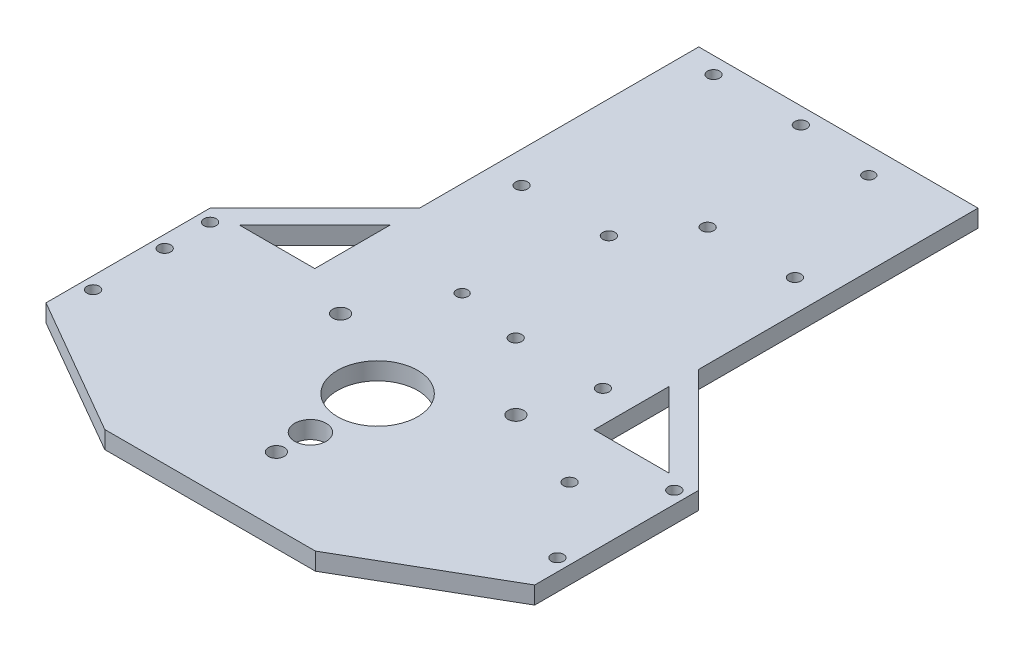
SolidWorks part; units mm, degrees
ref_plane "前视基准面" through (0, 0, 0) normal (0, 0, 1) x (1, 0, 0)
ref_plane "上视基准面" through (0, 0, 0) normal (0, 1, 0) x (1, 0, 0)
ref_plane "右视基准面" through (0, 0, 0) normal (1, 0, 0) x (0, 0, -1)
sketch "草图1" plane through (0, 0, 0) normal (0, 1, 0) x (1, 0, 0)
  line L1 (-40, 90) -> (40, 90)
  line L2 (-40, 90) -> (-40, -90)
  line L3 (-40, -90) -> (40, -90)
  line L4 (40, 90) -> (40, -90)
  line L5 (-40, 90) -> (40, -90) construction
  line L6 (-40, -90) -> (40, 90) construction
  point P0 (0, 0)
  dimension "D1" = 80
  dimension "D2" = 180
extrude "凸台-拉伸1" add sketch "草图1" along normal blind 5
sketch "草图2" plane through (0, 5, 0) normal (0, 1, 0) x (1, 0, 0)
  line L0 (40, -90) -> (40, 90) construction
  line L1 (-40, 90) -> (40, 90)
  line L3 (-40, 90) -> (40, 90)
  line L5 (-40, 38.4) -> (40, 38.4)
  line L6 (-40, 90) -> (40, 90)
  line L7 (-40, 90) -> (-40, 25.5)
  line L8 (-40, 25.5) -> (40, 25.5)
  line L9 (40, 90) -> (40, 25.5)
  line L10 (-40, 90) -> (-37, 90)
  line L11 (-40, 90) -> (-40, 25.5)
  line L12 (-40, 25.5) -> (-37, 25.5)
  line L13 (-37, 90) -> (-37, 25.5)
  line L14 (40, 90) -> (37, 90)
  line L15 (40, 90) -> (40, 25.5)
  line L16 (40, 25.5) -> (37, 25.5)
  line L17 (37, 90) -> (37, 25.5)
  line L18 (-37, 90) -> (0, 90)
  line L19 (-37, 90) -> (-37, 25.5)
  line L20 (-37, 25.5) -> (0, 25.5)
  line L21 (0, 90) -> (0, 25.5)
  line L22 (37, 25.5) -> (0, 25.5)
  line L23 (37, 25.5) -> (37, 90)
  line L24 (37, 90) -> (0, 90)
  line L25 (0, 25.5) -> (0, 90)
  line L26 (0, -13.2) -> (37, 51.3)
  line L27 (0, 51.3) -> (40, 51.3)
  line L28 (0, 51.3) -> (0, -13.2)
  line L29 (0, -13.2) -> (40, -13.2)
  line L30 (40, 51.3) -> (40, -13.2)
  line L31 (-37, 90) -> (0, 25.5)
  line L32 (-40, 90) -> (-40, -90) construction
  line L33 (-31, 30.25) -> (-6, 30.25)
  line L34 (-31, 30.25) -> (-31, 85.25)
  line L35 (-31, 85.25) -> (-6, 85.25)
  line L36 (-6, 30.25) -> (-6, 85.25)
  line L37 (-31, 30.25) -> (-6, 85.25) construction
  line L38 (-31, 85.25) -> (-6, 30.25) construction
  line L39 (6, 46.55) -> (31, 46.55)
  line L40 (6, 46.55) -> (6, -8.45)
  line L41 (6, -8.45) -> (31, -8.45)
  line L42 (31, 46.55) -> (31, -8.45)
  line L43 (6, 46.55) -> (31, -8.45) construction
  line L44 (6, -8.45) -> (31, 46.55) construction
  point P23 (-18.5, 57.75)
  point P29 (18.5, 19.05)
  dimension "D2" = 64.5
  dimension "D3" = 3
  dimension "D4" = 3
  dimension "D5" = 37
  dimension "D6" = 37
  dimension "D7" = 12.9
  dimension "D8" = 12.9
  dimension "D9" = 40
  dimension "D10" = 64.5
  dimension "D11" = 25
  dimension "D12" = 55
  dimension "D13" = 55
  dimension "D14" = 25
sketch "草图3" plane through (0, 5, 0) normal (0, 1, 0) x (1, 0, 0)
  point P0 (-31, 85.25)
  point P3 (-6, 85.25)
  point P6 (-6, 30.25)
  point P9 (-31, 30.25)
  point P12 (6, -8.45)
  point P15 (6, 46.55)
  point P18 (31, 46.55)
  point P21 (31, -8.45)
hole_wizard "孔1" positions "草图3" profile "草图4" legacy end condition through all
sketch "草图4" plane through (-31, 5, -85.25) normal (1, 0, 0) x (0, 0, 1)
  line L0 (0, 0) -> (0, 5)
  line L1 (0, 5) -> (1.75, 5)
  line L2 (1.75, 5) -> (1.75, 0)
  line L3 (1.75, 0) -> (0, 0)
  line L4 (0, 110) -> (0, -10) construction
  dimension "直径" = 3.5
  dimension "深度" = 5
sketch "草图5" plane through (0, 5, 0) normal (0, 1, 0) x (1, 0, 0)
  line L0 (40, -90) -> (40, 90) construction
  line L1 (-40, -90) -> (40, -90) construction
  line L2 (-40, -90) -> (-40, -10) construction
  line L3 (-40, -10) -> (40, -10) construction
  line L4 (40, -90) -> (40, -10) construction
  line L6 (0, -42) -> (0, -71)
  line L7 (0, -42) -> (-25.1147, -27.5)
  line L8 (0, -42) -> (25.1147, -27.5)
  circle A0 centre (0, -42) radius 29
  circle A1 centre (0, -42) radius 19.25
  dimension "D2" = 58
  dimension "D5" = 38.5
  dimension "D1" = 80
  dimension "D3" = 120
  dimension "D4" = 120
  dimension "D6" = 40
  dimension "D7" = 48
sketch "草图6" plane through (0, 5, 0) normal (0, 1, 0) x (1, 0, 0)
  point P0 (0, -71)
  point P3 (25.1147, -27.5)
  point P6 (-25.1147, -27.5)
hole_wizard "孔2" positions "草图6" profile "草图7" legacy end condition through all
sketch "草图7" plane through (0, 5, 71) normal (1, 0, 0) x (0, 0, 1)
  line L0 (0, 0) -> (0, 5)
  line L1 (0, 5) -> (2.25, 5)
  line L2 (2.25, 5) -> (2.25, 0)
  line L3 (2.25, 0) -> (0, 0)
  line L4 (0, 110) -> (0, -10) construction
  dimension "直径" = 4.5
  dimension "深度" = 5
sketch "草图8" plane through (0, 5, 0) normal (0, 1, 0) x (1, 0, 0)
  point P0 (0, -42)
hole_wizard "孔3" positions "草图8" profile "草图9" legacy end condition through all
sketch "草图9" plane through (0, 5, 42) normal (1, 0, 0) x (0, 0, 1)
  line L0 (0, 0) -> (0, 5)
  line L1 (0, 5) -> (11.5, 5)
  line L2 (11.5, 5) -> (11.5, 0)
  line L3 (11.5, 0) -> (0, 0)
  line L4 (0, 110) -> (0, -10) construction
  dimension "直径" = 23
  dimension "深度" = 5
sketch "草图10" plane through (0, 5, 0) normal (0, 1, 0) x (1, 0, 0)
  line L0 (0, -42) -> (0, -71) construction
  circle A0 centre (0, -42) radius 19.25 construction
  point P0 (0, -61.25)
hole_wizard "孔4" positions "草图10" profile "草图11" legacy end condition through all
sketch "草图11" plane through (0, 5, 61.25) normal (1, 0, 0) x (0, 0, 1)
  line L0 (0, 0) -> (0, 5)
  line L1 (0, 5) -> (4.5, 5)
  line L2 (4.5, 5) -> (4.5, 0)
  line L3 (4.5, 0) -> (0, 0)
  line L4 (0, 110) -> (0, -10) construction
  dimension "直径" = 9
  dimension "深度" = 5
sketch "草图13" plane through (0, 5, 0) normal (0, 1, 0) x (1, 0, 0)
  line L1 (-40, -90) -> (-70, -90)
  line L2 (-40, -90) -> (-40, -20)
  line L3 (-40, -20) -> (-70, -20)
  line L4 (-70, -90) -> (-70, -20)
  line L5 (40, -90) -> (70, -90)
  line L6 (40, -90) -> (40, -20)
  line L7 (40, -20) -> (70, -20)
  line L8 (70, -90) -> (70, -20)
  dimension "D1" = 30
  dimension "D2" = 70
  dimension "D3" = 30
  dimension "D4" = 70
extrude "凸台-拉伸2" add sketch "草图13" against normal blind 5
sketch "草图15" plane through (0, 5, 0) normal (0, 1, 0) x (1, 0, 0)
  line L0 (-70, -20) -> (-40, 10)
  line L1 (-40, 90) -> (-40, -20) construction
  line L2 (70, -20) -> (40, 10)
  line L3 (40, 51.3) -> (40, -13.2) construction
  line L4 (-40, 10) -> (-40, -20)
  line L5 (-40, -20) -> (-70, -20)
  line L6 (40, 10) -> (40, -20)
  line L7 (40, -20) -> (70, -20)
  line L8 (-61.5147, -20) -> (-40, 1.5147)
  line L9 (40, 1.5147) -> (61.5147, -20)
  line M24 (70, -20) -> (40, -20)
  line M27 (-40, 90) -> (-40, -20)
  dimension "D1" = 45
  dimension "D2" = 45
  dimension "D3" = 6
  dimension "D4" = 6
extrude "凸台-拉伸3" add sketch "草图15" against normal blind 5 contours L5 L8 L0 M27 | L6 L9 L2 M24
sketch "草图16" plane through (0, 5, 0) normal (0, 1, 0) x (1, 0, 0)
  line L0 (70, -90) -> (70, -20) construction
  line L1 (61.5147, -20) -> (40, -20) construction
  line L2 (-70, -20) -> (-70, -90) construction
  line L3 (-40, -20) -> (-61.5147, -20) construction
  point P0 (66.5, -57)
  point P1 (-66.5, -57)
  dimension "D1" = 3.5
  dimension "D2" = 37
  dimension "D3" = 3.5
  dimension "D4" = 37
sketch "草图17" plane through (0, 5, 0) normal (0, 1, 0) x (1, 0, 0)
  point P0 (-66.5, -57)
  point P3 (66.5, -57)
hole_wizard "孔5" positions "草图17" profile "草图18" legacy end condition through all
sketch "草图18" plane through (-66.5, 5, 57) normal (1, 0, 0) x (0, 0, 1)
  line L0 (0, 0) -> (0, 5)
  line L1 (0, 5) -> (1.75, 5)
  line L2 (1.75, 5) -> (1.75, 0)
  line L3 (1.75, 0) -> (0, 0)
  line L4 (0, 110) -> (0, -10) construction
  dimension "直径" = 3.5
  dimension "深度" = 5
sketch "草图19" plane through (0, 5, 0) normal (0, 1, 0) x (1, 0, 0)
  line L0 (-70, -67) -> (-30.1628, -90)
  line L1 (-70, -20) -> (-70, -90) construction
  line L2 (-70, -90) -> (70, -90) construction
  line L3 (-30.1628, -90) -> (-70, -90)
  line L4 (-70, -90) -> (-70, -67)
  line L5 (30.1628, -90) -> (70, -67)
  line L6 (70, -90) -> (70, -20) construction
  line L7 (70, -67) -> (70, -90)
  line L8 (70, -90) -> (30.1628, -90)
  dimension "D1" = 23
  dimension "D2" = 30
  dimension "D3" = 23
  dimension "D4" = 30
extrude "切除-拉伸1" cut sketch "草图19" against normal blind 5
sketch "草图20" plane through (0, 5, 0) normal (0, 1, 0) x (1, 0, 0)
  line L0 (-70, -20) -> (-70, -67) construction
  line L1 (-40, -20) -> (-61.5147, -20) construction
  line L2 (61.5147, -20) -> (40, -20) construction
  line L3 (70, -67) -> (70, -20) construction
  point P0 (-66.5, -23.5)
  point P1 (66.5, -23.5)
  dimension "D1" = 3.5
  dimension "D2" = 3.5
  dimension "D3" = 3.5
  dimension "D4" = 3.5
sketch "草图21" plane through (0, 5, 0) normal (0, 1, 0) x (1, 0, 0)
  point P0 (-66.5, -23.5)
  point P3 (66.5, -23.5)
hole_wizard "孔6" positions "草图21" profile "草图22" legacy end condition through all
sketch "草图22" plane through (-66.5, 5, 23.5) normal (1, 0, 0) x (0, 0, 1)
  line L0 (0, 0) -> (0, 5)
  line L1 (0, 5) -> (1.75, 5)
  line L2 (1.75, 5) -> (1.75, 0)
  line L3 (1.75, 0) -> (0, 0)
  line L4 (0, 110) -> (0, -10) construction
  dimension "直径" = 3.5
  dimension "深度" = 5
sketch "草图23" plane through (0, 5, 0) normal (0, 1, 0) x (1, 0, 0)
  line L0 (61.5147, -20) -> (40, -20) construction
  line L1 (70, -67) -> (70, -20) construction
  point P0 (49.5, -36.5)
  dimension "D1" = 16.5
  dimension "D2" = 20.5
hole_wizard "孔7" positions "草图23" profile "草图24" legacy end condition up to next
sketch "草图24" plane through (49.5, 5, 36.5) normal (1, 0, 0) x (0, 0, 1)
  line L0 (0, 0) -> (0, 5)
  line L1 (0, 5) -> (1.75, 5)
  line L2 (1.75, 5) -> (1.75, 0)
  line L3 (1.75, 0) -> (0, 0)
  line L4 (0, 110) -> (0, -10) construction
  dimension "直径" = 3.5
  dimension "深度" = 5
sketch "草图25" plane through (0, 5, 0) normal (0, 1, 0) x (1, 0, 0)
  line L0 (-40, 90) -> (40, 90) construction
  line L1 (-47.5, 90) -> (47.5, 90)
  line L2 (-47.5, 90) -> (-47.5, -10)
  line L3 (-47.5, -10) -> (47.5, -10)
  line L4 (47.5, 90) -> (47.5, -10)
  line L5 (40, 90) -> (40, 25.5) construction
  point P8 (-12.784, -5)
  point P9 (16.216, -2.5)
  point P10 (-12.906, 85)
  point P11 (16.216, 82.5)
  dimension "D1" = 95
  dimension "D2" = 100
  dimension "D3" = 7.5
  dimension "D4" = 5
  dimension "D5" = 34.716
  dimension "D6" = 7.5
  dimension "D7" = 31.284
  dimension "D8" = 34.594
  dimension "D9" = 5
  dimension "D10" = 31.284
  dimension "D11" = 7.5
sketch "草图26" plane through (0, 5, 0) normal (0, 1, 0) x (1, 0, 0)
  point P0 (-12.784, -5)
  point P3 (16.216, 82.5)
hole_wizard "孔8" positions "草图26" profile "草图27" legacy end condition up to next
sketch "草图27" plane through (-12.784, 5, 5) normal (1, 0, 0) x (0, 0, 1)
  line L0 (0, 0) -> (0, 5)
  line L1 (0, 5) -> (1.65, 5)
  line L2 (1.65, 5) -> (1.65, 0)
  line L3 (1.65, 0) -> (0, 0)
  line L4 (0, 110) -> (0, -10) construction
  dimension "直径" = 3.3
  dimension "深度" = 5
sketch "草图28" plane through (0, 5, 0) normal (0, 1, 0) x (1, 0, 0)
  line L0 (-40, -20) -> (-61.5147, -20) construction
  line L1 (-70, -20) -> (-70, -67) construction
  point P0 (-66.5, -36.5)
  dimension "D1" = 16.5
  dimension "D2" = 3.5
sketch "草图29" plane through (0, 5, 0) normal (0, 1, 0) x (1, 0, 0)
  point P0 (-66.5, -36.5)
hole_wizard "孔9" positions "草图29" profile "草图30" legacy end condition up to next
sketch "草图30" plane through (-66.5, 5, 36.5) normal (1, 0, 0) x (0, 0, 1)
  line L0 (0, 0) -> (0, 5)
  line L1 (0, 5) -> (1.75, 5)
  line L2 (1.75, 5) -> (1.75, 0)
  line L3 (1.75, 0) -> (0, 0)
  line L4 (0, 110) -> (0, -10) construction
  dimension "直径" = 3.5
  dimension "深度" = 5
